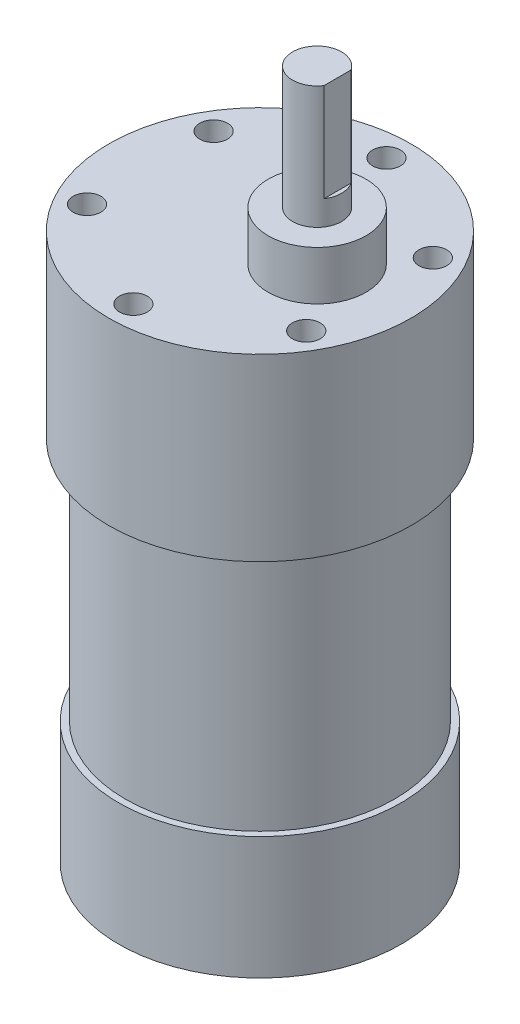
SolidWorks part; units mm, degrees
ref_plane "Front Plane" through (0, 0, 0) normal (0, 0, 1) x (1, 0, 0)
ref_plane "Top Plane" through (0, 0, 0) normal (0, 1, 0) x (1, 0, 0)
ref_plane "Right Plane" through (0, 0, 0) normal (1, 0, 0) x (0, 0, -1)
sketch "Sketch1" plane through (0, 0, 0) normal (0, 1, 0) x (1, 0, 0)
  circle A0 centre (0, 0) radius 16.5
extrude "Boss-Extrude1" add sketch "Sketch1" along normal blind 30
sketch "Sketch2" plane through (0, 0, 0) normal (0, -1, 0) x (1, 0, 0)
  circle A0 centre (0, 0) radius 2
extrude "Boss-Extrude2" add sketch "Sketch2" along normal blind 2
sketch "Sketch3" plane through (0, 30, 0) normal (0, 1, 0) x (1, 0, 0)
  circle A0 centre (0, 0) radius 18.5
extrude "Boss-Extrude3" add sketch "Sketch3" along normal blind 22
sketch "Sketch5" plane through (0, 52, 0) normal (0, 1, 0) x (1, 0, 0)
  line L0 (0, 0) -> (18.5, 0) construction
  line L1 (0, 0) -> (7, 0) construction
  circle A0 centre (0, 0) radius 18.5 construction
  circle A1 centre (7, 0) radius 6
extrude "Boss-Extrude4" add sketch "Sketch5" along normal blind 6
sketch "Sketch6" plane through (0, 58, 0) normal (0, 1, 0) x (1, 0, 0)
  circle A0 centre (7, 0) radius 3
extrude "Boss-Extrude5" add sketch "Sketch6" along normal blind 15
sketch "Sketch9" plane through (0, 73, 0) normal (0, 1, 0) x (1, 0, 0)
  line L0 (10, 0) -> (9.5, 0) construction
  line L1 (9.5, -1.6583) -> (9.5, 1.6583)
  circle A0 centre (7, 0) radius 3 construction
  arc A1 (9.5, 1.6583) -> (9.5, -1.6583) centre (7, 0) cw
  circle M2 centre (7, 0) radius 3
extrude "Cut-Extrude1" cut sketch "Sketch9" against normal blind 12 contours L0 A1 L1 | L0 L1 M2
sketch "Sketch10" plane through (0, 52, 0) normal (0, 1, 0) x (1, 0, 0)
  line L0 (15.5, 0) -> (-15.5, 0) construction
  line L1 (0, -15.5) -> (0, 15.5) construction
  line L2 (0, 0) -> (-13.4234, 7.75) construction
  line L3 (13.4234, 7.75) -> (0, 7.75) construction
  circle A0 centre (0, 0) radius 15.5 construction
  circle A1 centre (0, -15.5) radius 1 construction
  circle A2 centre (0, 15.5) radius 1 construction
  circle A3 centre (-13.4234, 7.75) radius 1 construction
  circle A4 centre (-13.4234, -7.75) radius 1 construction
  circle A5 centre (13.4234, 7.75) radius 1 construction
  circle A6 centre (13.4234, -7.75) radius 1 construction
hole_wizard "M3 Clearance Hole1" positions "Sketch14" profile "Sketch15" hole size "M3" standard "IS"
sketch "Sketch14" plane through (0, 52, 0) normal (0, 1, 0) x (1, 0, 0)
  point P0 (0, -15.5)
  point P8 (-13.4234, -7.75)
  point P12 (0, 15.5)
  point P16 (-13.4234, 7.75)
  point P20 (13.4234, -7.75)
  point P24 (13.4234, 7.75)
sketch "Sketch15" plane through (0, 52, 15.5) normal (1, 0, 0) x (0, 0, 1)
  line L0 (0, 0) -> (0, 11.0215)
  line L1 (0, 11.0215) -> (1.7, 10)
  line L2 (1.7, 10) -> (1.7, 0)
  line L5 (1.7, 0) -> (0, 0)
  line L10 (0, 11.0215) -> (-1.7, 10) construction
  line L11 (0, -6.35) -> (0, 107.95) construction
  dimension "Hole Dia." = 3.4
  dimension "Hole Depth" = 10
  dimension "Drill Angle" = 118
sketch "Sketch16" plane through (0, 0, 0) normal (0, -1, 0) x (1, 0, 0)
  circle A0 centre (0, 0) radius 17.3
extrude "Boss-Extrude6" add sketch "Sketch16" along normal blind 15
